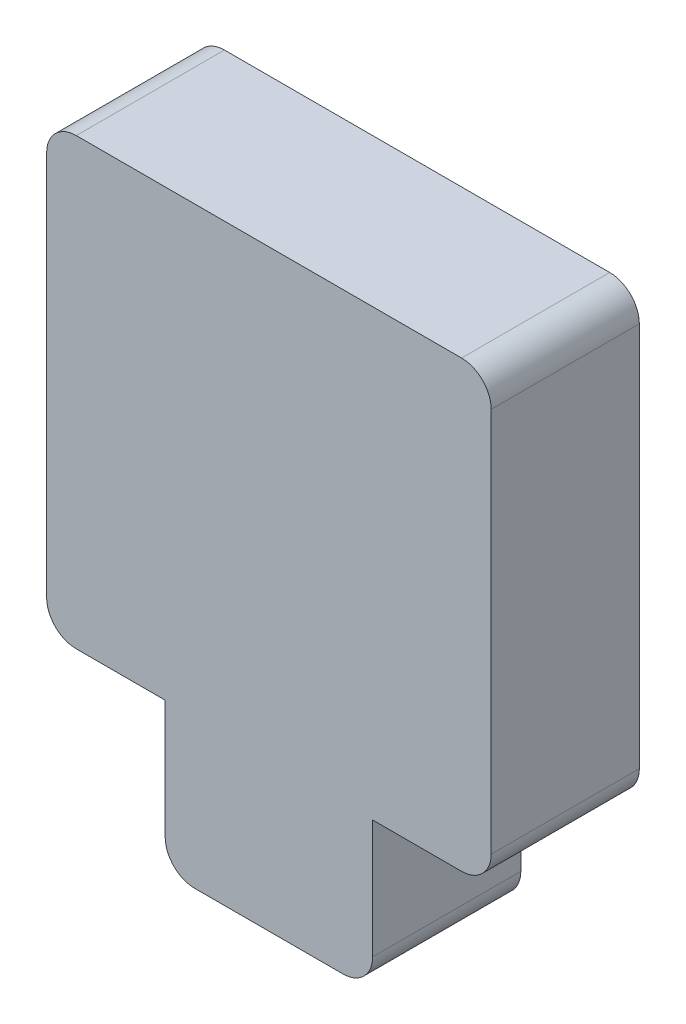
SolidWorks part; units mm, degrees
ref_plane "Front Plane" through (0, 0, 0) normal (0, 0, 1) x (1, 0, 0)
ref_plane "Top Plane" through (0, 0, 0) normal (0, 1, 0) x (1, 0, 0)
ref_plane "Right Plane" through (0, 0, 0) normal (1, 0, 0) x (0, 0, -1)
sketch "Sketch1" plane through (0, 0, 0) normal (0, 0, 1) x (1, 0, 0)
  line L1 (-7, 0) -> (7, 0)
  line L2 (-7, 0) -> (-7, -10)
  line L3 (-7, -10) -> (7, -10)
  line L4 (7, 0) -> (7, -10)
  line L5 (-7, 0) -> (7, -10) construction
  line L6 (-7, -10) -> (7, 0) construction
  line L7 (-15, 30) -> (15, 30)
  line L8 (-15, 30) -> (-15, 0)
  line L9 (-15, 0) -> (15, 0)
  line L10 (15, 30) -> (15, 0)
  line L11 (-15, 30) -> (15, 0) construction
  line L12 (-15, 0) -> (15, 30) construction
  point P0 (0, -5)
  point P5 (0, 15)
  dimension "D1" = 14
  dimension "D2" = 10
  dimension "D3" = 0
  dimension "D4" = 0
  dimension "D5" = 0
  dimension "D6" = 30
  dimension "D7" = 30
extrude "Boss-Extrude1" add sketch "Sketch1" along normal blind 10 contours L8 L7 L10 L9 | L2 L1 L4 L3
fillet "Fillet1" radius 2 6 edges at (7, -10, 5) (-7, -10, 5) (-15, 0, 5) (15, 0, 5) (15, 30, 5) (-15, 30, 5)
